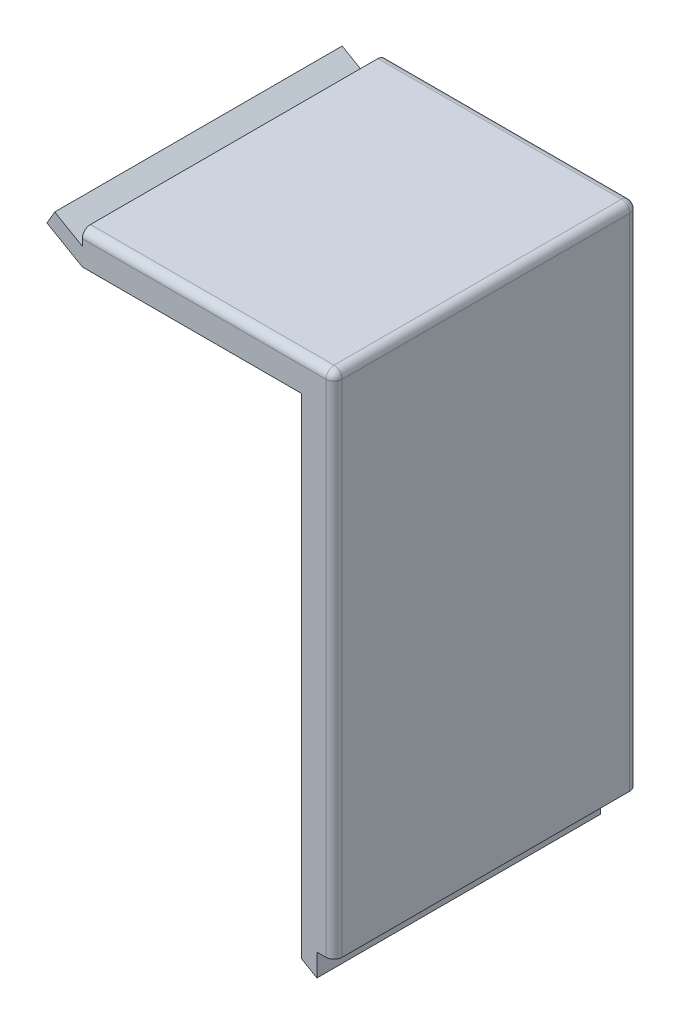
SolidWorks part; units mm, degrees
material "ABS"
ref_plane "前基準面" through (0, 0, 0) normal (0, 0, 1) x (1, 0, 0)
ref_plane "上基準面" through (0, 0, 0) normal (0, 1, 0) x (1, 0, 0)
ref_plane "右基準面" through (0, 0, 0) normal (1, 0, 0) x (0, 0, -1)
sketch "草圖1" plane through (0, 0, 0) normal (0, 0, 1) x (1, 0, 0)
  line L0 (35.0077, 40.3722) -> (54.4568, 40.3722)
  line L1 (54.4568, 40.3722) -> (69.5658, 14.2027)
  line L2 (69.5658, 14.2027) -> (59.8412, -2.6407)
  line L3 (59.8412, -2.6407) -> (35.0077, 40.3722)
  line L4 (46.5547, 40.3722) -> (65.6147, 7.3593)
  line L5 (69.5658, 14.2027) -> (104.2068, -5.7973)
  line L6 (104.2068, -5.7973) -> (104.2068, -4.7973)
  line L7 (104.2068, -4.7973) -> (116.2068, -4.7973)
  line L8 (116.2068, -4.7973) -> (116.2068, -12.7255)
  line L9 (116.2068, -12.7255) -> (104.2068, -5.7973)
  line L10 (54.4568, 40.3722) -> (54.4568, 119.9622)
  line L11 (54.4568, 119.9622) -> (116.2068, 119.9622)
  line L12 (116.2068, 119.9622) -> (116.2068, -4.7973)
  circle A0 centre (46.7546, 30.026) radius 2.1
  circle A1 centre (56.7546, 12.7055) radius 2.1
  dimension "D1" = 4.2
  dimension "D2" = 4.2
  dimension "D4" = 5
  dimension "D5" = 5
  dimension "D6" = 20
  dimension "D7" = 15.3462
  dimension "D8" = 11.7469
  dimension "D3" = 90
  dimension "D9" = 10
  dimension "D10" = 60
  dimension "D11" = 60
  dimension "D12" = 40
  dimension "D13" = 1
  dimension "D14" = 90
  dimension "D15" = 60
  dimension "D16" = 79.59
  dimension "D17" = 12
  dimension "D18" = 90
  dimension "D19" = 90
  dimension "D20" = 132.6877
  dimension "D21" = 61.75
extrude "填料-伸長1" add sketch "草圖1" along normal blind 10 contours L12 L11 L10 L1 L5 L6 L7 | L0 L4 L2 L1
sketch "草圖2" plane through (0, 0, 10) normal (0, 0, 1) x (1, 0, 0)
  line L0 (116.2068, -4.7973) -> (108.2068, -4.7973)
  line L1 (104.2068, -4.7973) -> (116.2068, -4.7973) construction
  line L2 (108.2068, -4.7973) -> (108.2068, 119.9622)
  line L3 (54.4568, 119.9622) -> (116.2068, 119.9622) construction
  line L4 (108.2068, 119.9622) -> (116.2068, 119.9622)
  line L5 (116.2068, 119.9622) -> (116.2068, -4.7973)
  line L6 (108.2068, 119.9622) -> (54.4568, 119.9622)
  line L7 (54.4568, 119.9622) -> (54.4568, 111.9622)
  line L8 (54.4568, 40.3722) -> (54.4568, 119.9622) construction
  line L9 (54.4568, 111.9622) -> (108.2068, 111.9622)
  line L10 (108.2068, 111.9622) -> (108.2068, 119.9622)
  line L11 (116.2068, 119.9622) -> (116.2068, -4.7973) construction
  dimension "D1" = 71.59
  dimension "D2" = 8
  dimension "D3" = 0
extrude "填料-伸長2" add sketch "草圖2" along normal blind 64.5
sketch "草圖4" plane through (0, -4.7973, 0) normal (0, -1, 0) x (1, 0, 0)
  line L0 (104.2068, 0) -> (116.2068, 0) construction
  line L1 (108.2068, 74.5) -> (112.0068, 74.5)
  line L2 (108.2068, 74.5) -> (108.2068, 5)
  line L3 (108.2068, 5) -> (112.0068, 5)
  line L4 (112.0068, 74.5) -> (112.0068, 5)
  dimension "D1" = 5
  dimension "D2" = 3.8
extrude "填料-伸長4" add sketch "草圖4" along normal blind 1
sketch "草圖5" plane through (0, 0, 5) normal (0, 0, -1) x (-1, 0, 0)
  line L0 (-108.2068, -5.7973) -> (-108.2068, -8.1067)
  line L1 (-108.2068, -8.1067) -> (-112.0068, -10.3006)
  line L2 (-112.0068, -10.3006) -> (-112.0068, -5.7973)
  line L3 (-112.0068, -5.7973) -> (-108.2068, -5.7973)
  line L4 (-69.5658, 14.2027) -> (-104.2068, -5.7973) construction
  dimension "D1" = 90
extrude "填料-伸長5" add sketch "草圖5" against normal up to surface (69.5 mm away) up to face at (97.7193, 55.3325, 74.5)
sketch "草圖6" plane through (0, 0, 74.5) normal (0, 0, 1) x (1, 0, 0)
  line L0 (54.4568, 111.9622) -> (50.9927, 113.9622)
  line L1 (50.9927, 113.9622) -> (54.4568, 119.9622)
  line L2 (54.4568, 119.9622) -> (54.4568, 111.9622)
  line L3 (69.5658, 14.2027) -> (104.2068, -5.7973) construction
  line L4 (52.8927, 117.2531) -> (54.6248, 116.2531)
  dimension "D1" = 3.8
extrude "填料-伸長6" add sketch "草圖6" against normal blind 70.5 contours L4 L1 L0 L2
fillet "圓角1" radius 2 5 edges at (116.2068, 57.5825, 0) (85.3318, 119.9622, 0) (116.2068, 119.9622, 37.25) (85.3318, 119.9622, 74.5) (116.2068, 57.5825, 74.5)
sketch "草圖7" plane through (-11.1025, 6.4101, 0) normal (-0.866, 0.5, 0) x (0, 0, 1)
  line L1 (74.5, 124.1905) -> (4, 124.1905)
  line L2 (74.5, 124.1905) -> (74.5, 127.9905)
  line L3 (74.5, 127.9905) -> (4, 127.9905)
  line L4 (4, 124.1905) -> (4, 127.9905)
extrude "填料-伸長7" add sketch "草圖7" along normal blind 6
sketch "草圖8" plane through (0, 0, 0) normal (0, 0, -1) x (-1, 0, 0)
  line L0 (-104.2068, -4.7973) -> (-102.4747, -4.7973)
  line L1 (-69.5658, 14.2027) -> (-104.2068, -5.7973) construction
  line L2 (-102.4747, -4.7973) -> (-104.2068, -5.7973)
  line L3 (-104.2068, -5.7973) -> (-104.2068, -4.7973)
extrude "除料-伸長1" cut sketch "草圖8" against normal up to next
